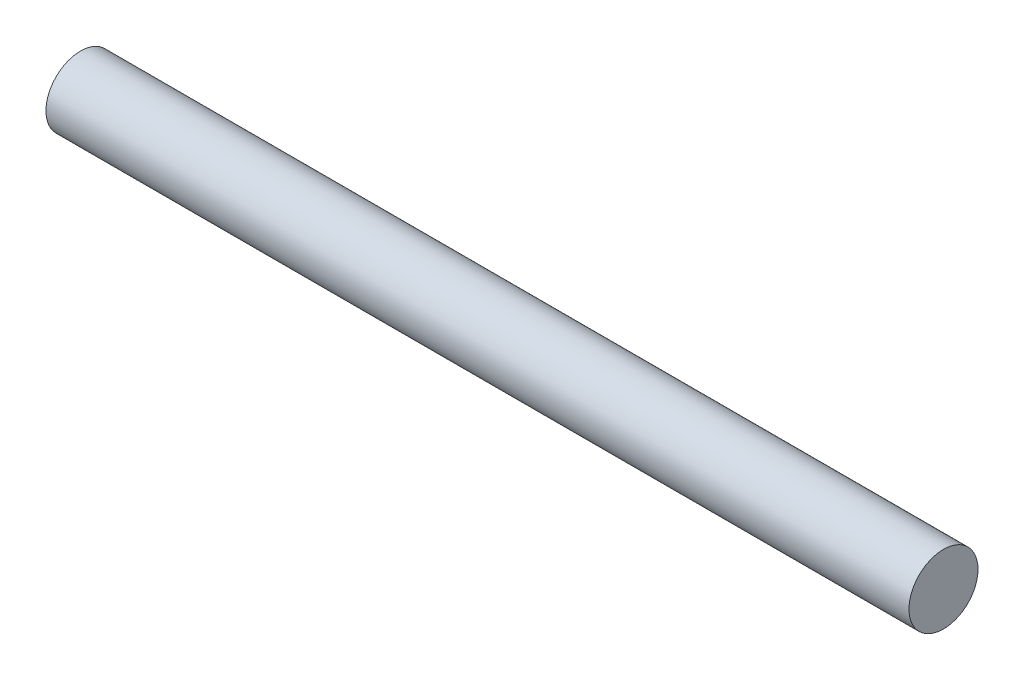
SolidWorks part; units mm, degrees
material "Stainless Steel (ferritic)"
ref_plane "Front Plane" through (0, 0, 0) normal (0, 0, 1) x (1, 0, 0)
ref_plane "Top Plane" through (0, 0, 0) normal (0, 1, 0) x (1, 0, 0)
ref_plane "Right Plane" through (0, 0, 0) normal (1, 0, 0) x (0, 0, -1)
sketch "Sketch1" plane through (0, 0, 0) normal (1, 0, 0) x (0, 0, -1)
  circle A0 centre (0, 0) radius 40
extrude "Boss-Extrude1" add sketch "Sketch1" along normal blind 1000
